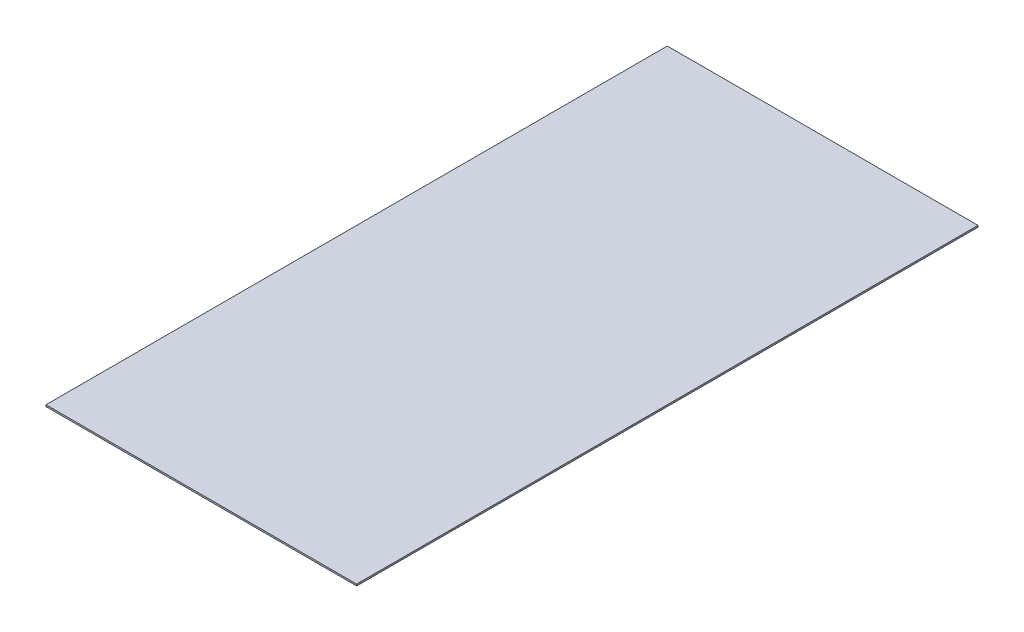
SolidWorks part; units mm, degrees
material "ASTM A36 Acero"
ref_plane "Alzado" through (0, 0, 0) normal (0, 0, 1) x (1, 0, 0)
ref_plane "Planta" through (0, 0, 0) normal (0, 1, 0) x (1, 0, 0)
ref_plane "Vista lateral" through (0, 0, 0) normal (1, 0, 0) x (0, 0, -1)
sketch "Croquis1" plane through (0, 0, 0) normal (0, 1, 0) x (1, 0, 0)
  line L1 (-609.6, -1219.2) -> (609.6, -1219.2)
  line L2 (-609.6, -1219.2) -> (-609.6, 1219.2)
  line L3 (-609.6, 1219.2) -> (609.6, 1219.2)
  line L4 (609.6, -1219.2) -> (609.6, 1219.2)
  line L5 (-609.6, -1219.2) -> (609.6, 1219.2) construction
  line L6 (-609.6, 1219.2) -> (609.6, -1219.2) construction
  point P0 (0, 0)
  dimension "D1" = 2438.4
  dimension "D2" = 1219.2
extrude "Saliente-Extruir1" add sketch "Croquis1" along normal blind 6.4
